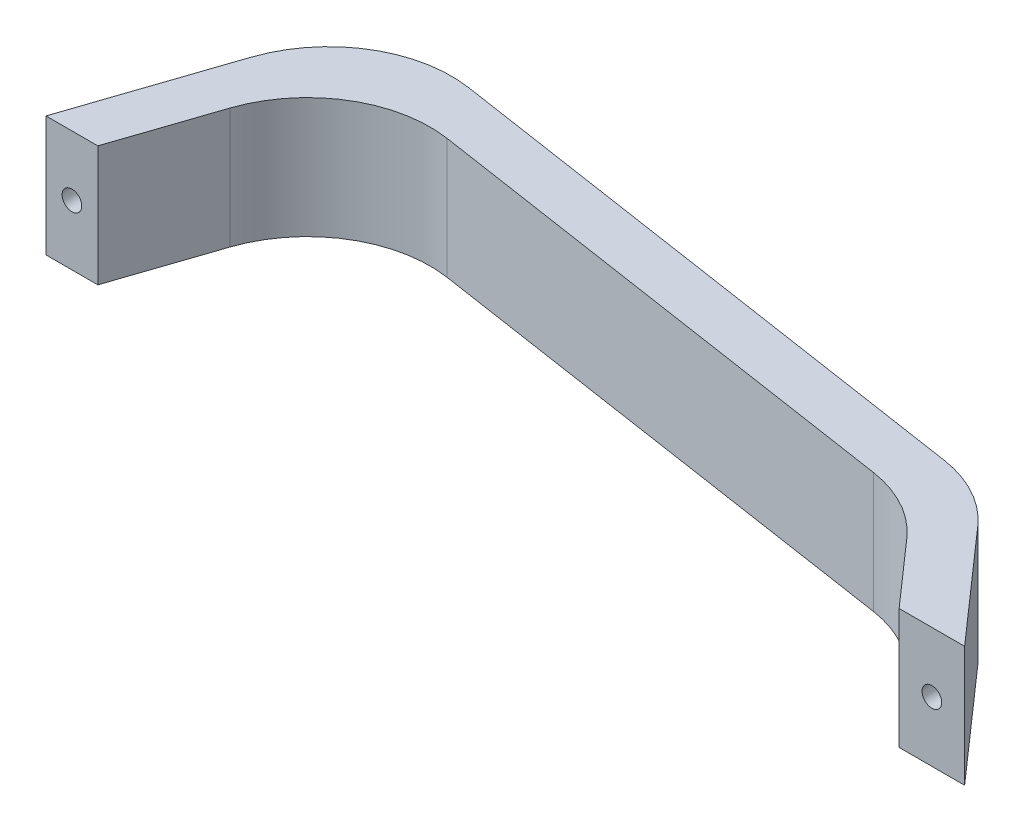
SolidWorks part; units mm, degrees
material "PC 高粘度"
ref_plane "前视基准面" through (0, 0, 0) normal (0, 0, 1) x (1, 0, 0)
ref_plane "上视基准面" through (0, 0, 0) normal (0, 1, 0) x (1, 0, 0)
ref_plane "右视基准面" through (0, 0, 0) normal (1, 0, 0) x (0, 0, -1)
sketch "草图1" plane through (0, 0, 0) normal (0, 1, 0) x (1, 0, 0)
  line L0 (-80, 0) -> (-66.5245, 40)
  line L1 (-66.5245, 40) -> (65.4389, 20)
  line L2 (65.4389, 20) -> (83.0601, 0)
  line L3 (-89.4767, 3.1926) -> (-73.3223, 51.1445)
  line L4 (-73.3223, 51.1445) -> (70.5359, 29.3417)
  line L5 (70.5359, 29.3417) -> (90.5632, 6.6108)
  line L6 (-80, 0) -> (-90.5522, 0)
  line L7 (-89.4767, 3.1926) -> (-90.5522, 0)
  line L8 (83.0601, 0) -> (96.3877, 0)
  line L9 (90.5632, 6.6108) -> (96.3877, 0)
  point P9 (-85.2761, 0)
  point P12 (89.7239, 0)
  dimension "D2" = 40
  dimension "D3" = 20
  dimension "D4" = 100
  dimension "D5" = 140
  dimension "D6" = 80
  dimension "D7" = 10
  dimension "D8" = 175
extrude "凸台-拉伸1" add sketch "草图1" along normal blind 24.5
fillet "圆角1" radius 25 4 edges at (65.4389, 12.25, -20) (70.5359, 12.25, -29.3417) (-73.3223, 12.25, -51.1445) (-66.5245, 12.25, -40)
sketch "草图2" plane through (0, 0, 0) normal (0, 0, 1) x (1, 0, 0)
  line L0 (-85.2761, 24.5) -> (-85.2761, 0) construction
  line L1 (-90.5522, 24.5) -> (-80, 24.5) construction
  line L2 (-90.5522, 0) -> (-80, 0) construction
  line L3 (-90.5522, 12.25) -> (-80, 12.25) construction
  line L4 (-90.5522, 24.5) -> (-90.5522, 0) construction
  line L5 (-80, 24.5) -> (-80, 0) construction
  line L6 (89.7239, 24.5) -> (89.7239, 0) construction
  line L7 (83.0601, 24.5) -> (96.3877, 24.5) construction
  line L8 (83.0601, 0) -> (96.3877, 0) construction
  line L9 (83.0601, 12.25) -> (96.3877, 12.25) construction
  line L10 (83.0601, 24.5) -> (83.0601, 0) construction
  line L11 (96.3877, 24.5) -> (96.3877, 0) construction
  circle A0 centre (-85.2761, 12.25) radius 2
  circle A1 centre (89.7239, 12.25) radius 2
  dimension "D1" = 4
  dimension "D2" = 4
extrude "切除-拉伸1" cut sketch "草图2" against normal blind 5
